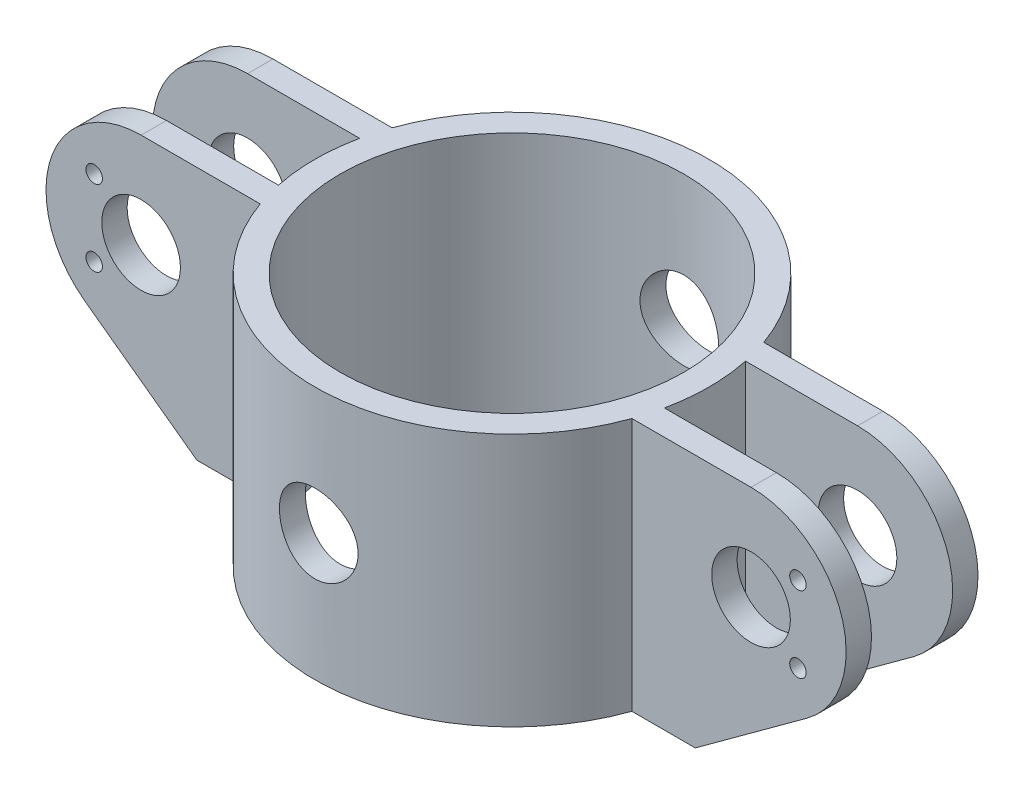
SolidWorks part; units mm, degrees
ref_plane "前视基准面" through (0, 0, 0) normal (0, 0, 1) x (1, 0, 0)
ref_plane "上视基准面" through (0, 0, 0) normal (0, 1, 0) x (1, 0, 0)
ref_plane "右视基准面" through (0, 0, 0) normal (1, 0, 0) x (0, 0, -1)
sketch "草图1" plane through (0, 0, 0) normal (0, 1, 0) x (1, 0, 0)
  circle A0 centre (0, 0) radius 135.5
  circle A1 centre (0, 0) radius 155.5
  dimension "D1" = 311
  dimension "D2" = 271
extrude "凸台-拉伸1" add sketch "草图1" along normal blind 200
ref_plane "基准面1" through (0, 0, 500) normal (0, 0, 1) x (1, 0, 0)
sketch "草图2" plane through (0, 0, 500) normal (0, 0, 1) x (1, 0, 0)
  line L0 (-1155.5, 100) -> (48844.5, 100) construction
  line L1 (-155.5, 200) -> (-155.5, 0) construction
  line L2 (0, -1000) -> (0, 49000) construction
  circle A0 centre (0, 100) radius 31
  point P7 (-155.5, 100)
  dimension "D1" = 62
extrude "切除-拉伸1" cut sketch "草图2" against normal through all
sketch "草图3" plane through (0, 200, 0) normal (0, 1, 0) x (1, 0, 0)
  line L0 (-1000, 0) -> (49000, 0) construction
  line L1 (146.5478, 52) -> (346.5478, 52)
  line L2 (146.5478, 52) -> (146.5478, 32)
  line L3 (146.5478, 32) -> (346.5478, 32)
  line L4 (346.5478, 52) -> (346.5478, 32)
  line L5 (146.5478, -32) -> (346.5478, -32)
  line L6 (146.5478, -32) -> (146.5478, -52)
  line L7 (146.5478, -52) -> (346.5478, -52)
  line L8 (346.5478, -32) -> (346.5478, -52)
  line L9 (-346.5478, 52) -> (-146.5478, 52)
  line L10 (-346.5478, 52) -> (-346.5478, 32)
  line L11 (-346.5478, 32) -> (-146.5478, 32)
  line L12 (-146.5478, 52) -> (-146.5478, 32)
  line L13 (-346.5478, -32) -> (-146.5478, -32)
  line L14 (-346.5478, -32) -> (-346.5478, -52)
  line L15 (-346.5478, -52) -> (-146.5478, -52)
  line L16 (-146.5478, -32) -> (-146.5478, -52)
  circle A0 centre (0, 0) radius 155.5 construction
  dimension "D1" = 20
  dimension "D2" = 200
  dimension "D3" = 64
extrude "凸台-拉伸2" add sketch "草图3" against normal blind 200
sketch "草图4" plane through (0, 0, 52) normal (0, 0, 1) x (1, 0, 0)
  line L0 (0, -1000) -> (0, 49000) construction
  line L1 (-346.5478, 200) -> (-146.5478, 200) construction
  line L2 (284.7464, 64.4422) -> (196.5478, 0)
  line L3 (146.5478, 0) -> (346.5478, 0) construction
  line L4 (196.5478, 0) -> (346.5478, 0)
  line L5 (346.5478, 0) -> (346.5478, 200)
  line L6 (346.5478, 200) -> (240.5, 200)
  line L7 (146.5478, 200) -> (346.5478, 200) construction
  line L8 (146.5478, 0) -> (146.5478, 200) construction
  line L9 (-284.7464, 64.4422) -> (-196.5478, 0)
  line L10 (-346.5478, 0) -> (-146.5478, 0) construction
  line L11 (-196.5478, 0) -> (-346.5478, 0)
  line L12 (-346.5478, 0) -> (-346.5478, 200)
  line L13 (-346.5478, 200) -> (-240.5, 200)
  circle A0 centre (-240.5, 125) radius 31
  circle A1 centre (240.5, 125) radius 31
  arc A2 (240.5, 200) -> (284.7464, 64.4422) centre (240.5, 125) cw
  arc A3 (-240.5, 200) -> (-284.7464, 64.4422) centre (-240.5, 125) ccw
  dimension "D1" = 62
  dimension "D2" = 75
  dimension "D3" = 481
  dimension "D4" = 50
extrude "切除-拉伸2" cut sketch "草图4" against normal through all
sketch "草图5" plane through (0, 0, 52) normal (0, 0, 1) x (1, 0, 0)
  line L0 (277.5, -852.2968) -> (277.5, 49147.7032) construction
  line L1 (-759.5, 125) -> (49240.5, 125) construction
  line L2 (-277.5, -821.3558) -> (-277.5, 49178.6442) construction
  circle A0 centre (240.5, 125) radius 31 construction
  circle A1 centre (277.5, 155) radius 6.5
  circle A2 centre (277.5, 95) radius 6.5
  circle A3 centre (-240.5, 125) radius 31 construction
  circle A4 centre (-277.5, 155) radius 6.5
  circle A5 centre (-277.5, 95) radius 6.5
  dimension "D3" = 13
  dimension "D4" = 37
  dimension "D1" = 37
  dimension "D2" = 60
extrude "切除-拉伸3" cut sketch "草图5" against normal blind 20
